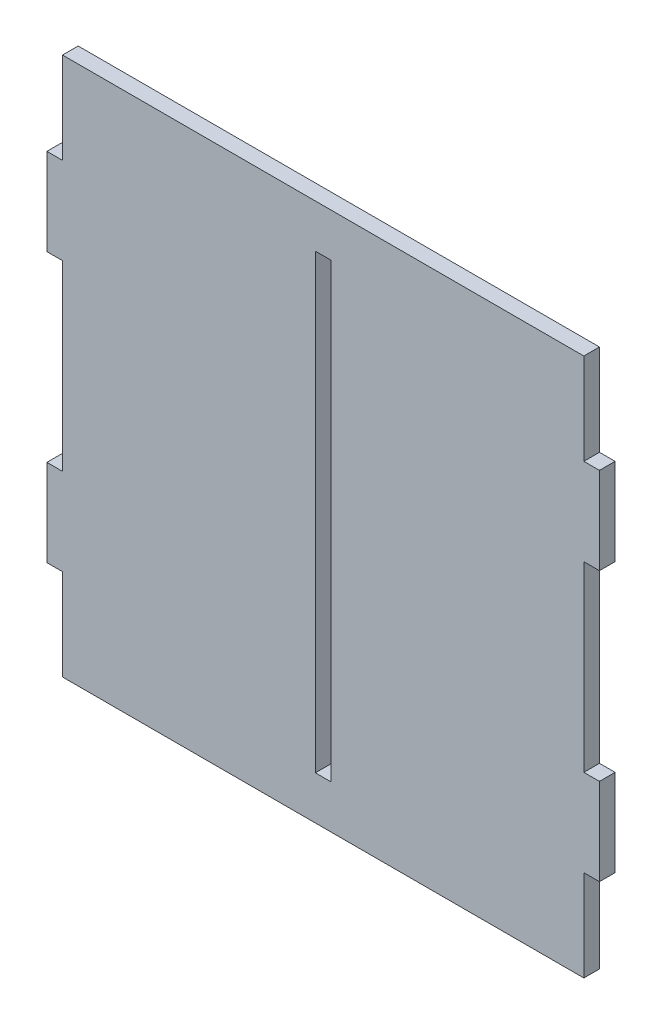
SolidWorks part; units mm, degrees
ref_plane "Front Plane" through (0, 0, 0) normal (0, 0, 1) x (1, 0, 0)
ref_plane "Top Plane" through (0, 0, 0) normal (0, 1, 0) x (1, 0, 0)
ref_plane "Right Plane" through (0, 0, 0) normal (1, 0, 0) x (0, 0, -1)
sketch "Sketch1" plane through (0, 0, 0) normal (0, 0, 1) x (1, 0, 0)
  line L0 (0, 0) -> (0, -105)
  line L5 (0, 0) -> (600, 0)
  line L6 (0, -205) -> (0, -415)
  line L7 (-18, -105) -> (0, -105)
  line L8 (-18, -105) -> (-18, -205)
  line L13 (-18, -205) -> (0, -205)
  line L21 (600, -620) -> (600, -515)
  line L25 (-18, -415) -> (0, -415)
  line L26 (-18, -515) -> (-18, -415)
  line L27 (-18, -515) -> (0, -515)
  line L28 (0, -620) -> (600, -620)
  line L29 (0, -620) -> (0, -515)
  line L30 (618, -105) -> (600, -105)
  line L31 (618, -105) -> (618, -205)
  line L32 (618, -205) -> (600, -205)
  line L33 (618, -415) -> (600, -415)
  line L34 (618, -515) -> (618, -415)
  line L35 (618, -515) -> (600, -515)
  line L36 (600, 0) -> (600, -105)
  line L37 (600, -205) -> (600, -415)
  point P2 (0, -91.1017)
  point P15 (600, -91.1017)
  point P27 (600, -368.8983)
  point P28 (0, -368.8983)
  dimension "D1" = 100
  dimension "D2" = 100
  dimension "D3" = 105
  dimension "D4" = 620
  dimension "D5" = 18
  dimension "D6" = 18
  dimension "D9" = 210
  dimension "D10" = 105
  dimension "D11" = 600
  dimension "D12" = 600
extrude "Boss-Extrude3" add sketch "Sketch1" along normal blind 18 contours L5 L36 L30 L31 L32 L37 L33 L34 L35 L21 L28 L29 L27 L26 L25 L6 L13 L8 L7 L0
sketch "Sketch2" plane through (0, 0, 0) normal (0, 0, -1) x (-1, 0, 0)
  line L0 (-300, 0) -> (-300, -620) construction
  line L1 (0, 0) -> (-600, 0) construction
  line L2 (0, -620) -> (-600, -620) construction
  line L3 (-291, -50) -> (-309, -50)
  line L5 (-291, -50) -> (-291, -570)
  line L6 (-291, -570) -> (-309, -570)
  line L7 (-309, -50) -> (-309, -570)
  line L8 (-291, -50) -> (-309, -570) construction
  line L9 (-291, -570) -> (-309, -50) construction
  point P6 (-300, -310)
  point P11 (-304.6315, -50)
  dimension "D1" = 18
  dimension "D2" = 50
extrude "Cut-Extrude1" cut sketch "Sketch2" against normal through all both and the other way through all contours L3 L7 L6 L5
